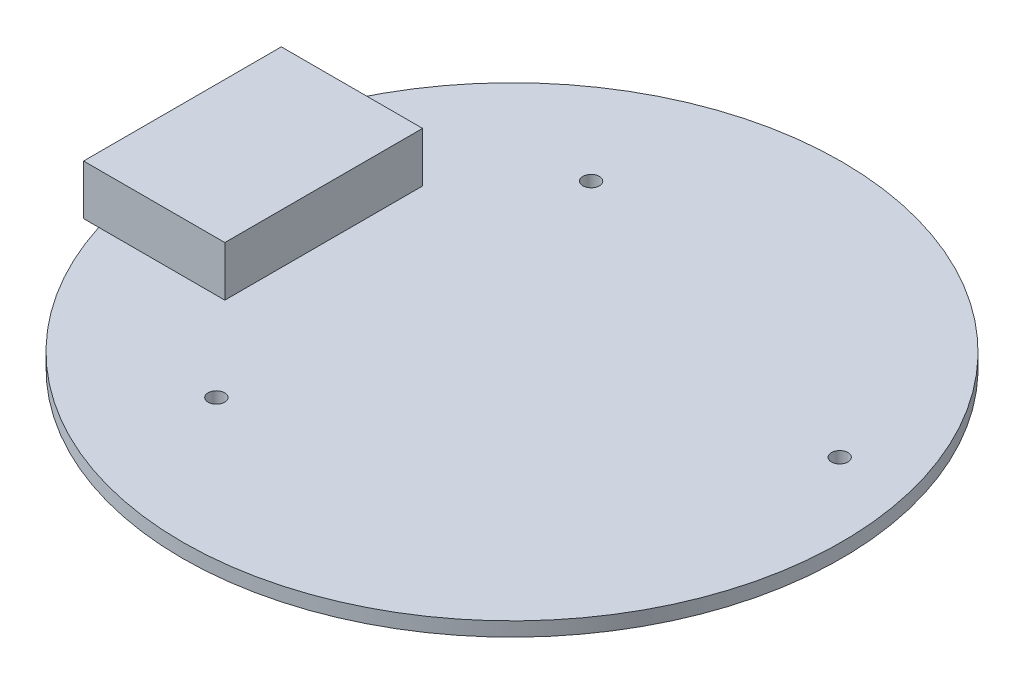
SolidWorks part; units mm, degrees
ref_plane "Front Plane" through (0, 0, 0) normal (0, 0, 1) x (1, 0, 0)
ref_plane "Top Plane" through (0, 0, 0) normal (0, 1, 0) x (1, 0, 0)
ref_plane "Right Plane" through (0, 0, 0) normal (1, 0, 0) x (0, 0, -1)
sketch "Sketch1" plane through (0, 0, 0) normal (0, 1, 0) x (1, 0, 0)
  circle A0 centre (0, 0) radius 35
  dimension "D1" = 70
extrude "Boss-Extrude1" add sketch "Sketch1" along normal blind 1.5
sketch "Sketch2" plane through (0, 1.5, 0) normal (0, 1, 0) x (1, 0, 0)
  line L0 (0, 35) -> (0, -35) construction
  line L1 (0, -0.825) -> (0, 0.825) construction
  line L3 (-0.825, 0) -> (0.825, 0) construction
  line L4 (35, 0) -> (-35, 0) construction
  circle A0 centre (0, 0) radius 35 construction
  circle A1 centre (-11.5, 19.9) radius 1
  circle A2 centre (27.1, 7.7) radius 1
  circle A3 centre (-11.5, -19.9) radius 1
  point P6 (-11.5, -19.9)
  point P11 (-11.5, 19.9)
  point P12 (27.1, 7.7)
  dimension "D7" = 2
  dimension "D1" = 11.5
  dimension "D2" = 19.9
  dimension "D3" = 19.9
  dimension "D4" = 11.5
  dimension "D5" = 7.7
  dimension "D6" = 27.1
sketch "Sketch4" plane through (0, 1.5, 0) normal (0, 1, 0) x (1, 0, 0)
  line L0 (-20, 0) -> (-35, 0) construction
  line L1 (-20, 10.5) -> (-35, 10.5)
  line L2 (-20, 10.5) -> (-20, -10.5)
  line L3 (-20, -10.5) -> (-35, -10.5)
  line L4 (-35, 10.5) -> (-35, -10.5)
  line L5 (35, 0) -> (-35, 0) construction
  line L6 (0, -0.825) -> (0, 0.825) construction
  point P6 (-27.5, 0)
  dimension "D1" = 21
  dimension "D2" = 15
  dimension "D3" = 20
extrude "Boss-Extrude2" add sketch "Sketch4" along normal blind 5.3
hole_wizard "Tap Drill for M2.2x0.45 Tap1" positions "3DSketch2" profile "Sketch5" hole size "M2.2x0.45" standard "ANSI Metric" end condition through all
sketch3d "3DSketch2"
  point P0 (-11.5, 1.5, -19.9)
  point P3 (27.1, 1.5, -7.7)
  point P6 (-11.5, 1.5, 19.9)
sketch "Sketch5" plane through (-11.5, 1.5, -19.9) normal (1, 0, 0) x (0, 0, 1)
  line L0 (0, 0) -> (0, 1.5)
  line L1 (0, 1.5) -> (0.875, 1.5)
  line L2 (0.875, 1.5) -> (0.875, 0)
  line L5 (0.875, 0) -> (0, 0)
  line L11 (0, -6.35) -> (0, 107.95) construction
  dimension "Thru Hole Dia." = 1.75
  dimension "Thru Hole Depth" = 1.5
